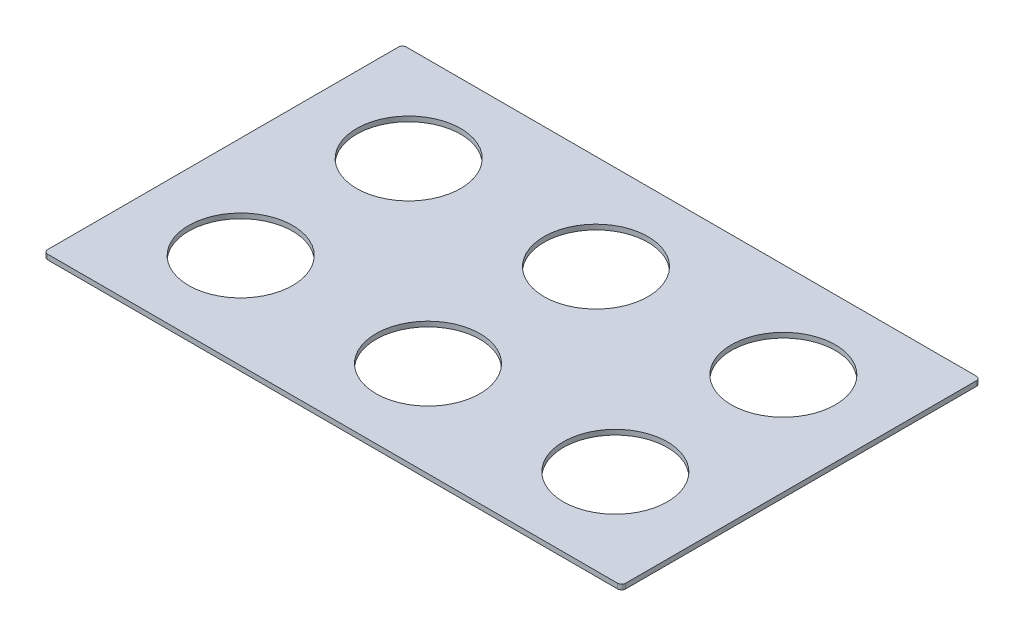
SolidWorks part; units mm, degrees
material "Acrylic (Medium-high impact)"
ref_plane "Front" through (0, 0, 0) normal (0, 0, 1) x (1, 0, 0)
ref_plane "Top" through (0, 0, 0) normal (0, 1, 0) x (1, 0, 0)
ref_plane "Right" through (0, 0, 0) normal (1, 0, 0) x (0, 0, -1)
sketch "Sketch1" plane through (0, 0, 0) normal (0, 1, 0) x (1, 0, 0)
  line L1 (-184.15, -114.3) -> (184.15, -114.3)
  line L2 (-184.15, -114.3) -> (-184.15, 114.3)
  line L3 (-184.15, 114.3) -> (184.15, 114.3)
  line L4 (184.15, -114.3) -> (184.15, 114.3)
  line L5 (-184.15, -114.3) -> (184.15, 114.3) construction
  line L6 (-184.15, 114.3) -> (184.15, -114.3) construction
  circle A0 centre (119.38, 53.5305) radius 33.147
  circle A1 centre (0, 53.5305) radius 33.147
  circle A2 centre (-119.38, 53.5305) radius 33.147
  circle A3 centre (-119.38, -53.5305) radius 33.147
  circle A4 centre (0, -53.5305) radius 33.147
  circle A5 centre (119.38, -53.5305) radius 33.147
  circle A6 centre (119.38, 53.5305) radius 33.02 construction
  point P0 (0, 0)
  dimension "D3" = 0.127
  dimension "D1" = 368.3
  dimension "D2" = 228.6
extrude "Boss-Extrude1" add sketch "Sketch1" along normal blind 3.175
fillet "Fillet1" radius 2.54 4 edges at (-184.15, 1.5875, 114.3) (184.15, 1.5875, 114.3) (184.15, 1.5875, -114.3) (-184.15, 1.5875, -114.3)
